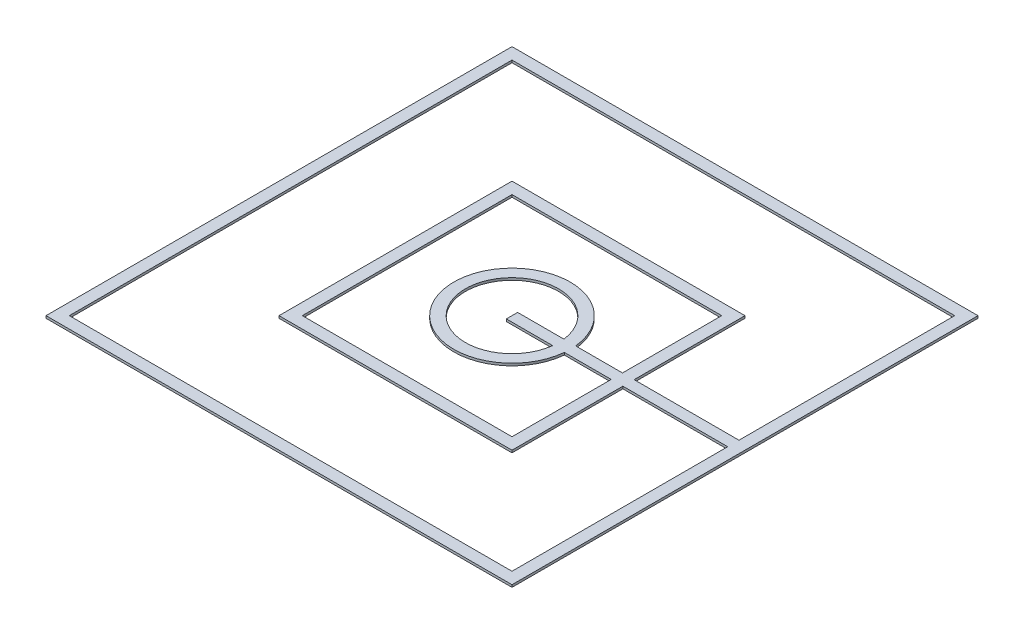
SolidWorks part; units mm, degrees
ref_plane "Ebene vorne" through (0, 0, 0) normal (0, 0, 1) x (1, 0, 0)
ref_plane "Ebene oben" through (0, 0, 0) normal (0, 1, 0) x (1, 0, 0)
ref_plane "Ebene rechts" through (0, 0, 0) normal (1, 0, 0) x (0, 0, -1)
sketch "Skizze1" plane through (0, 0, 0) normal (0, 1, 0) x (1, 0, 0)
  line L0 (0, 0) -> (100, 0) construction
  line L1 (100, 100) -> (-100, 100)
  line L2 (100, 100) -> (100, -100)
  line L3 (100, -100) -> (-100, -100)
  line L4 (-100, 100) -> (-100, -100)
  line L5 (100, 100) -> (-100, -100) construction
  line L6 (100, -100) -> (-100, 100) construction
  line L7 (95, 95) -> (-95, 95)
  line L8 (95, 95) -> (95, 2.4179)
  line L9 (95, -95) -> (-95, -95)
  line L10 (-95, 95) -> (-95, -95)
  line L11 (95, 95) -> (-95, -95) construction
  line L12 (95, -95) -> (-95, 95) construction
  line L13 (50, 50) -> (-50, 50)
  line L14 (50, 50) -> (50, 2.4179)
  line L15 (50, -50) -> (-50, -50)
  line L16 (-50, 50) -> (-50, -50)
  line L17 (50, 50) -> (-50, -50) construction
  line L18 (50, -50) -> (-50, 50) construction
  line L19 (45, 45) -> (-45, 45)
  line L20 (45, 45) -> (45, 2.4179)
  line L21 (45, -45) -> (-45, -45)
  line L22 (-45, 45) -> (-45, -45)
  line L23 (45, 45) -> (-45, -45) construction
  line L24 (45, -45) -> (-45, 45) construction
  line L25 (0, -2.4179) -> (19.8533, -2.4179)
  line L26 (0, 2.4179) -> (19.8533, 2.4179)
  line L27 (50, -2.4179) -> (50, -50)
  line L28 (45, -2.4179) -> (45, -45)
  line L29 (24.8828, 2.4179) -> (45, 2.4179)
  line L30 (24.8828, -2.4179) -> (45, -2.4179)
  line L31 (50, 2.4179) -> (95, 2.4179)
  line L32 (50, -2.4179) -> (95, -2.4179)
  line L33 (95, -2.4179) -> (95, -95)
  line L34 (0, 2.4179) -> (0, -2.4179)
  arc A0 (24.8828, 2.4179) -> (24.8828, -2.4179) centre (0, 0) ccw
  arc A1 (19.8533, 2.4179) -> (19.8533, -2.4179) centre (0, 0) ccw
  point P0 (0, 0)
  point P6 (0, 0)
  point P11 (0, 0)
  point P16 (0, 0)
  dimension "D6" = 50
  dimension "D7" = 5
  dimension "D1" = 200
  dimension "D2" = 5
  dimension "D3" = 100
  dimension "D4" = 5
  dimension "D5" = 5
extrude "Aufsatz-Linear austragen1" add sketch "Skizze1" along normal blind 1
